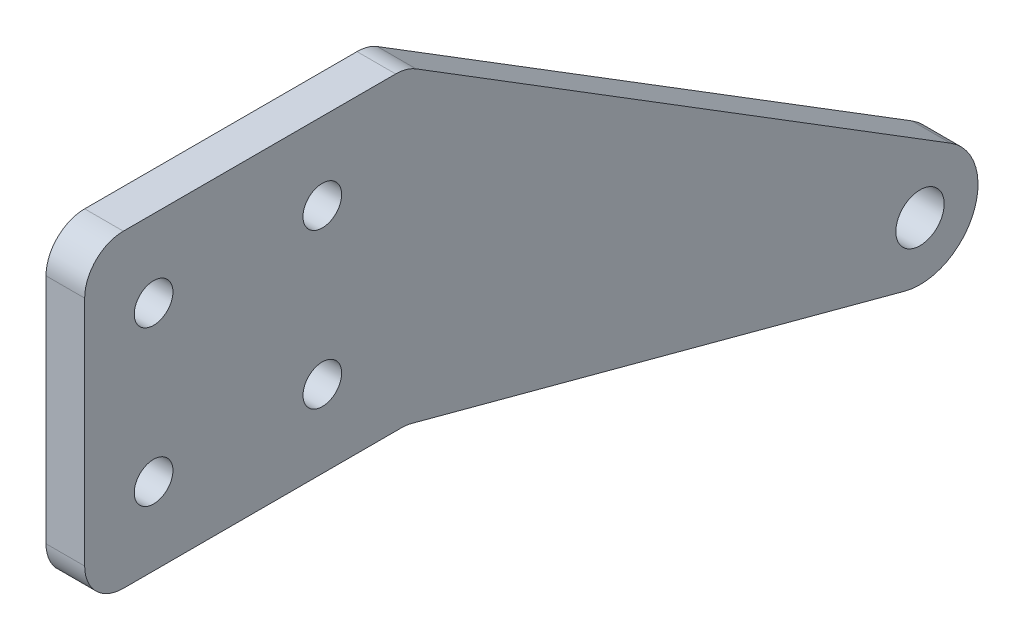
SolidWorks part; units mm, degrees
ref_plane "Front Plane" through (0, 0, 0) normal (0, 0, 1) x (1, 0, 0)
ref_plane "Top Plane" through (0, 0, 0) normal (0, 1, 0) x (1, 0, 0)
ref_plane "Right Plane" through (0, 0, 0) normal (1, 0, 0) x (0, 0, -1)
sketch "Sketch1" plane through (0, 0, 0) normal (1, 0, 0) x (0, 0, -1)
  line L1 (76.2, 788.1561) -> (76.2, 737.3561) construction
  line L3 (76.2, 788.1561) -> (76.2, 737.3561) construction
  line L6 (23.324, 737.3561) -> (23.324, 788.1561)
  line L7 (23.324, 788.1561) -> (76.2, 788.1561)
  line L8 (23.324, 737.3561) -> (76.2, 737.3561)
  line L9 (20.784, 781.8061) -> (20.784, 737.7456) construction
  line L10 (165.5056, 732.75) -> (76.2, 788.1561)
  line L11 (158.0212, 715.4551) -> (76.2, 737.3561)
  line L12 (20.784, 781.8061) -> (20.784, 737.7456) construction
  circle A0 centre (34.638, 775.4561) radius 2.6035 construction
  circle A1 centre (62.346, 775.4561) radius 2.6035 construction
  circle A2 centre (34.638, 750.0561) radius 2.6035 construction
  circle A3 centre (62.346, 750.0561) radius 2.6035 construction
  circle A4 centre (34.638, 775.4561) radius 2.6035 construction
  circle A5 centre (62.346, 775.4561) radius 2.6035 construction
  circle A6 centre (34.638, 750.0561) radius 2.6035 construction
  circle A7 centre (62.346, 750.0561) radius 2.6035 construction
  circle A8 centre (-17.316, 762.7561) radius 2.6035 construction
  circle A9 centre (-17.316, 762.7561) radius 2.6035 construction
  circle A10 centre (160.484, 724.6561) radius 3.9687
  arc A11 (158.0212, 715.4551) -> (165.5056, 732.75) centre (160.484, 724.6561) ccw
  circle A12 centre (62.346, 750.0561) radius 3.175
  circle A13 centre (34.638, 750.0561) radius 3.175
  circle A14 centre (34.638, 775.4561) radius 3.175
  circle A15 centre (62.346, 775.4561) radius 3.175
  dimension "D3" = 7.9375
  dimension "D4" = 9.525
  dimension "D5" = 6.35
  dimension "D2" = 177.8
  dimension "D6" = 38.1
  dimension "D1" = 2.54
extrude "Boss-Extrude1" add sketch "Sketch1" against normal blind 6.35 from surface at -38.1 contours L11 A11 L10 L7 L6 L8 A4 A5 A6 A7 A10
fillet "Fillet1" radius 6.35 4 edges at (-41.275, 788.1561, -23.324) (-41.275, 788.1561, -76.2) (-41.275, 737.3561, -23.324) (-41.275, 737.3561, -76.2)
